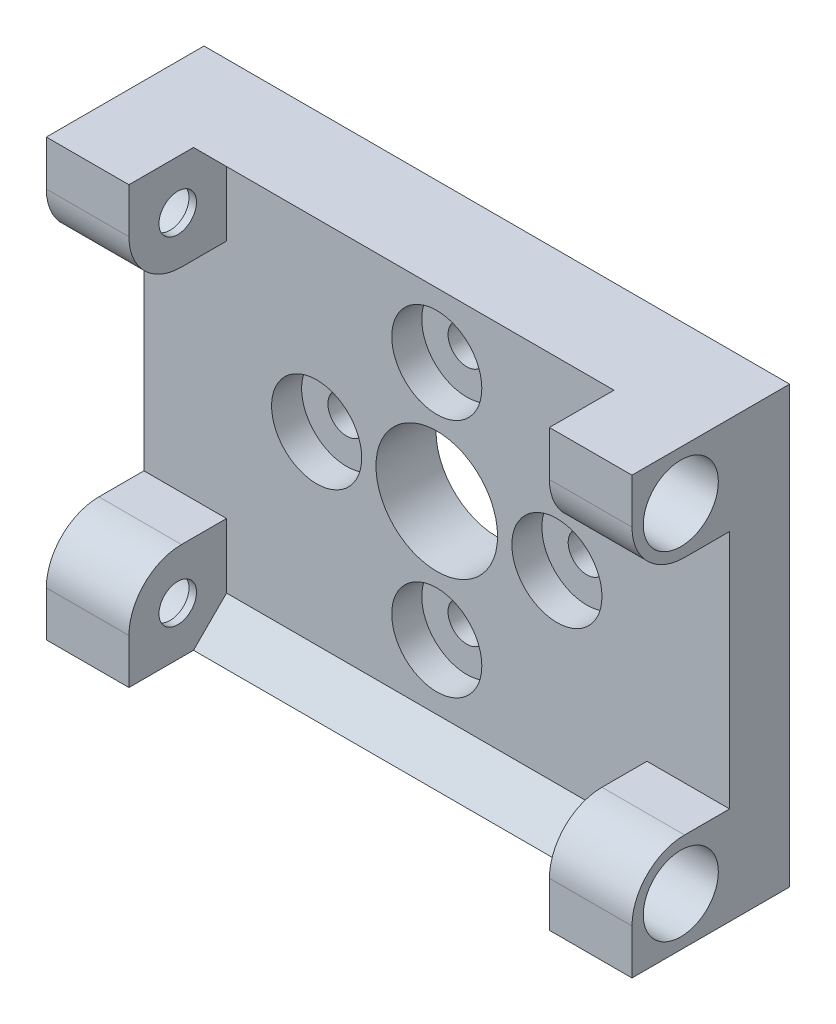
SolidWorks part; units mm, degrees
ref_plane "Front Plane" through (0, 0, 0) normal (0, 0, 1) x (1, 0, 0)
ref_plane "Top Plane" through (0, 0, 0) normal (0, 1, 0) x (1, 0, 0)
ref_plane "Right Plane" through (0, 0, 0) normal (1, 0, 0) x (0, 0, -1)
sketch "Sketch1" plane through (0, 0, 0) normal (0, 0, 1) x (1, 0, 0)
  line L5 (19.5, 0.8564) -> (-19.5, -22.8564) construction
  line L6 (19.5, -22.8564) -> (-19.5, 0.8564) construction
  line L7 (19.5, -22.8564) -> (-19.5, -22.8564)
  line L8 (19.5, -22.8564) -> (19.5, 0.8564)
  line L9 (19.5, 0.8564) -> (-19.5, 0.8564)
  line L10 (-19.5, -22.8564) -> (-19.5, 0.8564)
  line L11 (19.5, -22.8564) -> (-19.5, 0.8564) construction
  line L12 (19.5, 0.8564) -> (-19.5, -22.8564) construction
  arc A5 (1.25, -19) -> (-1.25, -19) centre (0, -19) ccw construction
  arc A6 (-1.25, -19) -> (1.25, -19) centre (0, -19) ccw construction
  arc A7 (1.25, -19) -> (-1.25, -19) centre (0, -19) ccw
  arc A8 (-1.25, -19) -> (1.25, -19) centre (0, -19) ccw
  arc A9 (-6.75, -11) -> (-9.25, -11) centre (-8, -11) ccw construction
  arc A10 (-6.75, -11) -> (-9.25, -11) centre (-8, -11) ccw
  arc A11 (-9.25, -11) -> (-6.75, -11) centre (-8, -11) ccw construction
  arc A12 (-9.25, -11) -> (-6.75, -11) centre (-8, -11) ccw
  arc A13 (1.25, -3) -> (-1.25, -3) centre (0, -3) ccw construction
  arc A14 (-1.25, -3) -> (1.25, -3) centre (0, -3) ccw construction
  arc A15 (1.25, -3) -> (-1.25, -3) centre (0, -3) ccw
  arc A16 (-1.25, -3) -> (1.25, -3) centre (0, -3) ccw
  arc A17 (9.25, -11) -> (6.75, -11) centre (8, -11) ccw construction
  arc A18 (6.75, -11) -> (9.25, -11) centre (8, -11) ccw construction
  arc A19 (9.25, -11) -> (6.75, -11) centre (8, -11) ccw
  arc A20 (6.75, -11) -> (9.25, -11) centre (8, -11) ccw
  point P0 (0, -11)
  point P8 (0, -11)
extrude "Boss-Extrude1" add sketch "Sketch1" along normal blind 2
sketch "Sketch9" plane through (0, 0, 2) normal (0, 0, 1) x (1, 0, 0)
  circle A0 centre (0, -11) radius 4.05
extrude "Cut-Extrude6" cut sketch "Sketch9" against normal blind 5
sketch "Sketch10" plane through (-19.5, 0, 0) normal (-1, 0, 0) x (0, 0, 1)
  line L0 (4.2, 3.5) -> (8.5, 3.5)
  line L1 (8.5, 3.5) -> (8.5, 0.5)
  line L2 (5, -3) -> (2, -3)
  line L3 (2, 0.8564) -> (2, -22.8564) construction
  line L4 (2, -3) -> (5, -3) construction
  line L5 (2, -3) -> (2, 0.8564)
  line L6 (2, 0.8564) -> (0, 0.8564)
  line L7 (0, 0.8564) -> (0, 3.5)
  line L8 (4.2, 3.5) -> (0, 3.5)
  line L9 (2, -11) -> (11.2, -11) construction
  line L10 (11.2, -17.2) -> (11.2, -4.8) construction
  line L11 (5, -19) -> (2, -19)
  line L12 (2, -19) -> (2, -22.8564)
  line L13 (2, -22.8564) -> (0, -22.8564)
  line L14 (0, -22.8564) -> (0, -25.5)
  line L15 (4.2, -25.5) -> (0, -25.5)
  line L16 (4.2, -25.5) -> (8.5, -25.5)
  line L17 (8.5, -25.5) -> (8.5, -22.5)
  arc A0 (5, -3) -> (8.5, 0.5) centre (5, 0.5) ccw construction
  arc A1 (5, -3) -> (8.5, 0.5) centre (5, 0.5) ccw
  circle A2 centre (5.25, 0.25) radius 1.25
  circle A3 centre (5.25, -22.25) radius 1.25
  arc A4 (5, -19) -> (8.5, -22.5) centre (5, -22.5) cw
  dimension "D1" = 2.5
extrude "Boss-Extrude5" add sketch "Sketch10" against normal up to surface (5.5 mm away)
sketch "Sketch11" plane through (-19.5, 0, 0) normal (-1, 0, 0) x (0, 0, 1)
  line L0 (3.2, -11) -> (11.2, -11) construction
  line L1 (3.2, -4.8) -> (3.2, -17.2) construction
  line L2 (11.2, -17.2) -> (11.2, -4.8) construction
  circle A0 centre (5.25, 0.25) radius 2.5
  circle A1 centre (5.25, -22.25) radius 2.5
  dimension "D1" = 5
extrude "Cut-Extrude7" cut sketch "Sketch11" against normal blind 5
sketch "Sketch12" plane through (19.5, 0, 0) normal (1, 0, 0) x (0, 0, -1)
  line L4 (-5, -3) -> (-2, -3)
  line L6 (-5, -3) -> (-2, -3)
  line L8 (-2, -3) -> (-2, -19)
  line L12 (0, -25.5) -> (0, 3.5)
  line L14 (-8.5, 3.5) -> (-8.5, 0.5)
  line L15 (-8.5, 3.5) -> (-8.5, 0.5)
  line L16 (-2, -3) -> (-2, -19)
  line L20 (0, -25.5) -> (0, 3.5)
  line L24 (0, 3.5) -> (-8.5, 3.5)
  line L25 (0, 3.5) -> (-8.5, 3.5)
  line L26 (-8.5, -25.5) -> (0, -25.5)
  line L27 (-8.5, -25.5) -> (0, -25.5)
  line L28 (-8.5, -22.5) -> (-8.5, -25.5)
  line L29 (-8.5, -22.5) -> (-8.5, -25.5)
  line L30 (-2, -19) -> (-5, -19)
  line L31 (-2, -19) -> (-5, -19)
  circle A0 centre (-5.25, -22.25) radius 2.5 construction
  circle A1 centre (-5.25, 0.25) radius 2.5 construction
  circle A6 centre (-5.25, -22.25) radius 2.5
  circle A7 centre (-5.25, 0.25) radius 2.5
  arc A8 (-8.5, 0.5) -> (-5, -3) centre (-5, 0.5) ccw
  arc A9 (-8.5, 0.5) -> (-5, -3) centre (-5, 0.5) ccw
  arc A10 (-5, -19) -> (-8.5, -22.5) centre (-5, -22.5) ccw
  arc A11 (-5, -19) -> (-8.5, -22.5) centre (-5, -22.5) ccw
  dimension "D1" = 0
extrude "Boss-Extrude6" add sketch "Sketch12" against normal up to surface (5.5 mm away) contours L20 L25 L15 A9 L6 L16 L31 A11 L29 L27 | A6 | A7
sketch "Sketch13" plane through (14, 0, 0) normal (-1, 0, 0) x (0, 0, 1)
  line L0 (0, 3.5) -> (4.2, 3.5)
  line L1 (0, 3.5) -> (8.5, 3.5) construction
  line L2 (4.2, 3.5) -> (2, 1.3) construction
  line L3 (4.2, 3.5) -> (2, 1.3)
  line L4 (2, 1.3) -> (2, 0.8564)
  line L5 (2, 0.8564) -> (0, 0.8564)
  line L6 (0, 0.8564) -> (0, 3.5)
  line L7 (3.2, -11) -> (11.2, -11) construction
  line L8 (3.2, -4.8) -> (3.2, -17.2) construction
  line L9 (11.2, -17.2) -> (11.2, -4.8) construction
  line L10 (2, -22.8564) -> (0, -22.8564)
  line L11 (2, -23.3) -> (2, -22.8564)
  line L12 (4.2, -25.5) -> (2, -23.3)
  line L13 (0, -25.5) -> (4.2, -25.5)
  line L14 (0, -22.8564) -> (0, -25.5)
extrude "Boss-Extrude7" add sketch "Sketch13" along normal up to surface (28 mm away) up to face at (-14, 0.3554, 3.8178)
sketch "Sketch14" plane through (0, 0, 0) normal (0, 0, -1) x (-1, 0, 0)
  line L4 (19.5, 3.5) -> (-19.5, 3.5)
  line L5 (-19.5, 3.5) -> (-19.5, -25.5)
  line L6 (-19.5, -25.5) -> (19.5, -25.5)
  line L7 (19.5, -25.5) -> (19.5, 3.5)
  line L8 (19.5, 3.5) -> (-19.5, 3.5)
  line L9 (-19.5, 3.5) -> (-19.5, -25.5)
  line L10 (-19.5, -25.5) -> (19.5, -25.5)
  line L11 (19.5, -25.5) -> (19.5, 3.5)
  circle A0 centre (0, -19) radius 1.25 construction
  circle A1 centre (8, -11) radius 1.25 construction
  circle A2 centre (0, -3) radius 1.25 construction
  circle A3 centre (0, -11) radius 4.05 construction
  circle A4 centre (-8, -11) radius 1.25 construction
  circle A5 centre (0, -19) radius 1.25
  circle A6 centre (8, -11) radius 1.25
  circle A7 centre (0, -3) radius 1.25
  circle A8 centre (0, -11) radius 4.05
  circle A9 centre (-8, -11) radius 1.25
  dimension "D1" = 0
extrude "Boss-Extrude8" add sketch "Sketch14" along normal blind 2
sketch "Sketch15" plane through (0, 0, 2) normal (0, 0, 1) x (1, 0, 0)
  circle A0 centre (0, -3) radius 3
  circle A1 centre (8, -11) radius 3
  circle A2 centre (0, -19) radius 3
  circle A3 centre (-8, -11) radius 3
  point P12 (0, -11)
  dimension "D1" = 6
  dimension "D2" = 4
extrude "Cut-Extrude8" cut sketch "Sketch15" against normal blind 2
